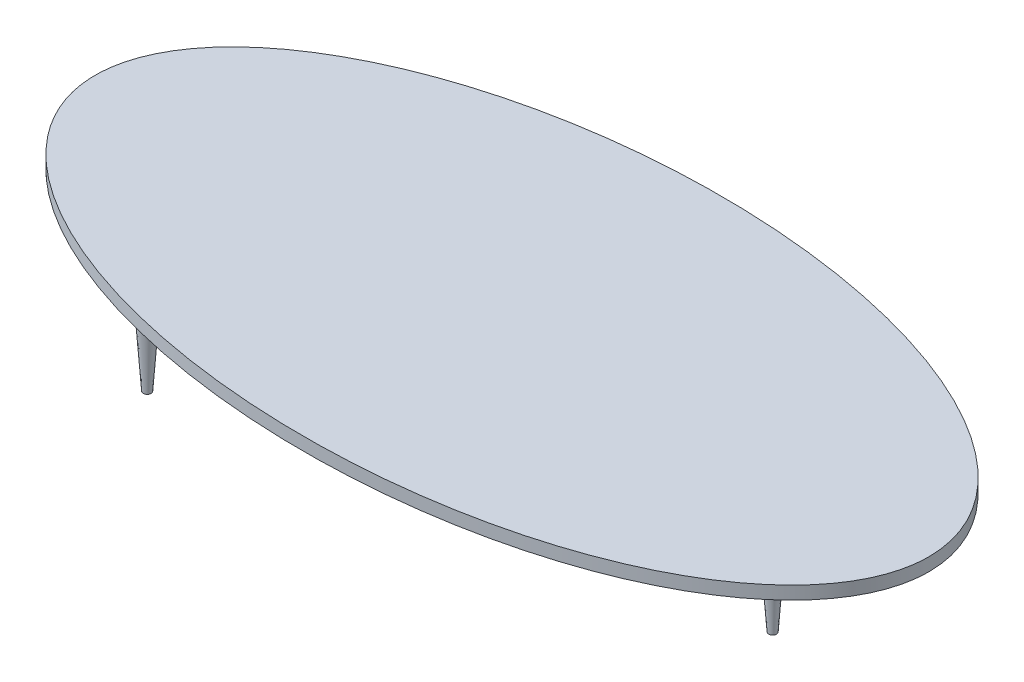
SolidWorks part; units mm, degrees
ref_plane "Front Plane" through (0, 0, 0) normal (0, 0, 1) x (1, 0, 0)
ref_plane "Top Plane" through (0, 0, 0) normal (0, 1, 0) x (1, 0, 0)
ref_plane "Right Plane" through (0, 0, 0) normal (1, 0, 0) x (0, 0, -1)
sketch "Sketch2" plane through (0, 0, 0) normal (0, 1, 0) x (1, 0, 0)
  line L0 (0, 0) -> (2438.4, 0) construction
  line L1 (0, 0) -> (-2438.4, 0) construction
  line L2 (0, 0) -> (0, 1219.2) construction
  ellipse E0 centre (0, 0) end of major axis (2438.4, 0) minor radius 1219.2
  dimension "D1" = 2438.4
  dimension "D2" = 1219.2
extrude "Boss-Extrude2" add sketch "Sketch2" along normal blind 76.2
sketch "Sketch3" plane through (0, 0, 0) normal (0, -1, 0) x (-1, 0, 0)
  line L1 (1524, 609.6) -> (-1524, 609.6) construction
  line L2 (1524, 609.6) -> (1524, -609.6) construction
  line L3 (1524, -609.6) -> (-1524, -609.6) construction
  line L4 (-1524, 609.6) -> (-1524, -609.6) construction
  line L5 (1524, 609.6) -> (-1524, -609.6) construction
  line L6 (1524, -609.6) -> (-1524, 609.6) construction
  circle A0 centre (1524, -609.6) radius 76.2
  circle A1 centre (1524, 609.6) radius 76.2
  circle A2 centre (-1524, 0) radius 76.2
  point P0 (0, 0)
  dimension "D3" = 152.4
  dimension "D1" = 1219.2
  dimension "D2" = 3048
extrude "Boss-Extrude3" add sketch "Sketch3" along normal blind 762 draft 4
